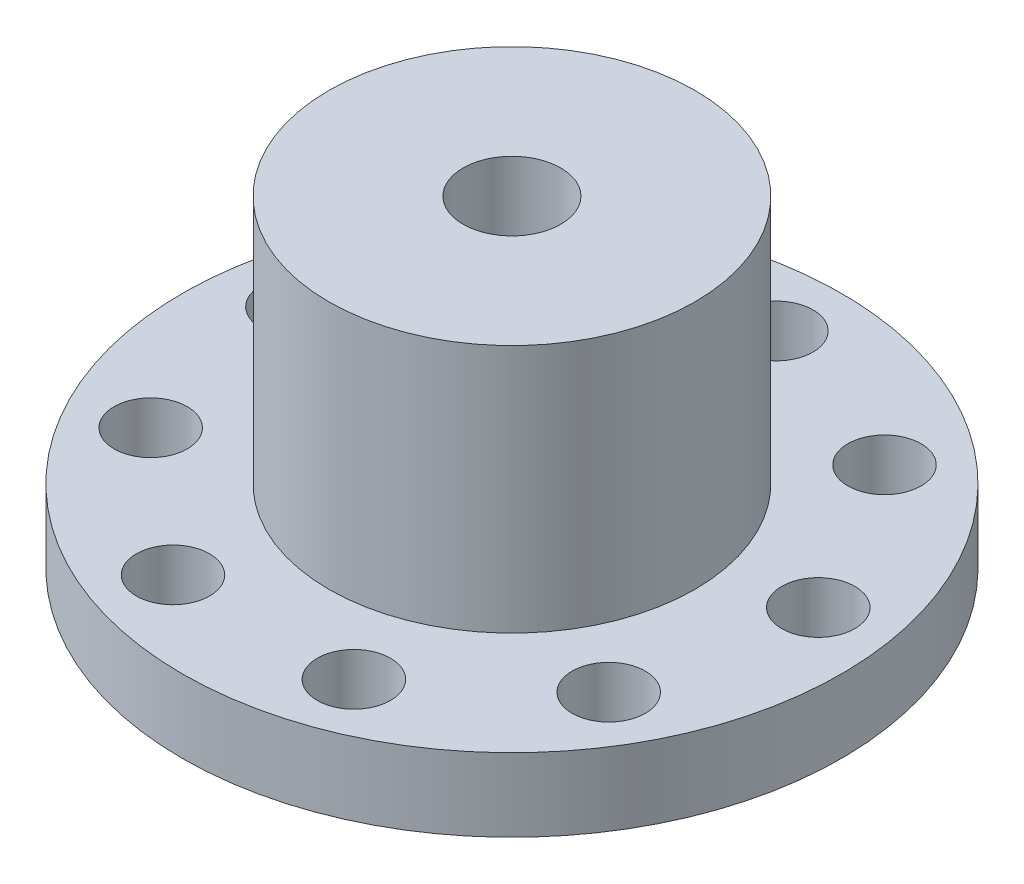
SolidWorks part; units mm, degrees
ref_plane "前视基准面" through (0, 0, 0) normal (0, 0, 1) x (1, 0, 0)
ref_plane "上视基准面" through (0, 0, 0) normal (0, 1, 0) x (1, 0, 0)
ref_plane "右视基准面" through (0, 0, 0) normal (1, 0, 0) x (0, 0, -1)
sketch "草图1" plane through (0, 0, 0) normal (0, 1, 0) x (1, 0, 0)
  line L0 (0, 21.6648) -> (0, 0) construction
  circle A0 centre (0, 0) radius 27
  circle A1 centre (0, 21.6648) radius 3
  circle A2 centre (13.9259, 16.5962) radius 3
  circle A3 centre (21.3357, 3.7621) radius 3
  circle A4 centre (18.7623, -10.8324) radius 3
  circle A5 centre (7.4098, -20.3583) radius 3
  circle A6 centre (-7.4098, -20.3583) radius 3
  circle A7 centre (-18.7623, -10.8324) radius 3
  circle A8 centre (-21.3357, 3.7621) radius 3
  circle A9 centre (-13.9259, 16.5962) radius 3
  circle A10 centre (0, 0) radius 4
  dimension "D1" = 6
  dimension "D3" = 54
  dimension "D4" = 8
  dimension "22.6" = 21.6648
  dimension "D2" = 9
extrude "凸台-拉伸1" add sketch "草图1" along normal blind 6
sketch "草图3" plane through (0, 6, 0) normal (0, 1, 0) x (1, 0, 0)
  circle A0 centre (0, 0) radius 15
  circle A1 centre (0, 0) radius 4 construction
  circle A2 centre (0, 0) radius 4
  dimension "D1" = 11
extrude "凸台-拉伸2" add sketch "草图3" along normal blind 20.4
ref_plane "基准面1" through (0, 0, 0) normal (0, 0, 1) x (0, 1, 0)
sketch "草图5" plane through (0, 0, 0) normal (0, 0, 1) x (0, 1, 0)
  line L0 (26.4, -15) -> (26.4, 15) construction
  circle A0 centre (16.2, 0) radius 2.5
  dimension "D2" = 5
  dimension "D1" = 10.2
extrude "切除-拉伸1" cut sketch "草图5" against normal through all
